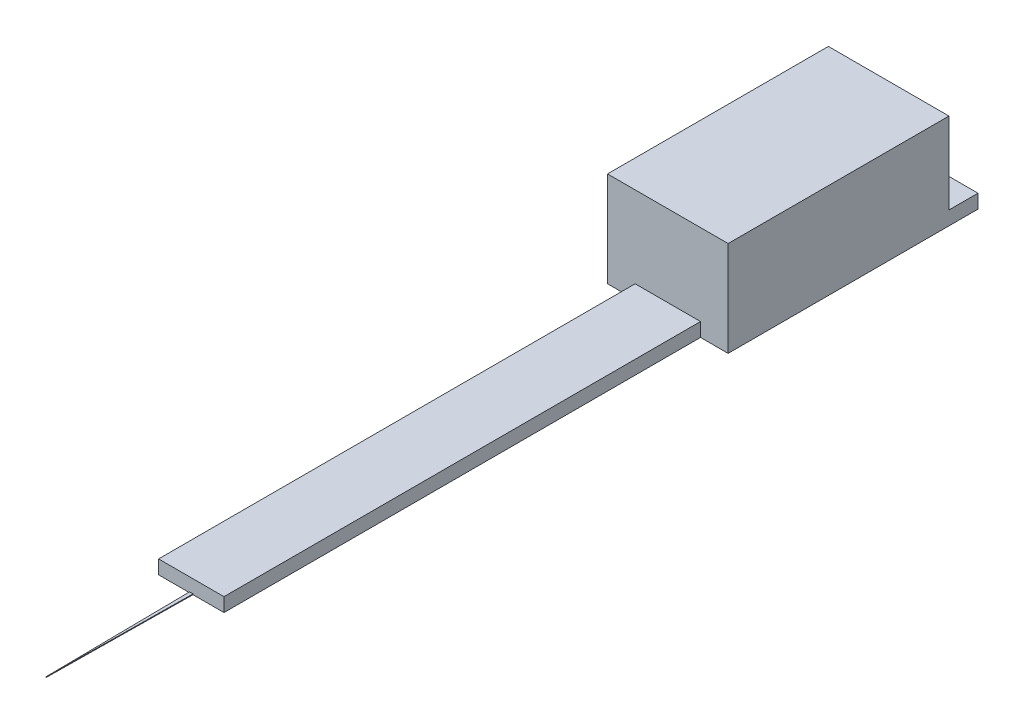
SolidWorks part; units mm, degrees
ref_plane "Front Plane" through (0, 0, 0) normal (0, 0, 1) x (1, 0, 0)
ref_plane "Top Plane" through (0, 0, 0) normal (0, 1, 0) x (1, 0, 0)
ref_plane "Right Plane" through (0, 0, 0) normal (1, 0, 0) x (0, 0, -1)
sketch "Sketch1" plane through (0, 0, 0) normal (0, 1, 0) x (1, 0, 0)
  line L0 (0, 0) -> (0.12, 10)
  line L1 (0.12, 10) -> (2.25, 10)
  line L2 (2.25, 10) -> (2.25, 42.8)
  line L3 (2.25, 42.8) -> (4.15, 42.8)
  line L4 (4.15, 42.8) -> (4.15, 60)
  line L5 (4.15, 60) -> (-4.15, 60)
  line L6 (0, -14.5849) -> (0, 93.9914) construction
  line L7 (-4.15, 42.8) -> (-4.15, 60)
  line L8 (-2.25, 42.8) -> (-4.15, 42.8)
  line L9 (-2.25, 10) -> (-2.25, 42.8)
  line L10 (-0.12, 10) -> (-2.25, 10)
  line L11 (0, 0) -> (-0.12, 10)
  point P11 (0, 60)
  dimension "D1" = 2.25
  dimension "D2" = 4.15
  dimension "D3" = 60
  dimension "D4" = 10
  dimension "D5" = 0.12
  dimension "D6" = 17.2
extrude "Extrude1" add sketch "Sketch1" along normal blind 0.05
sketch "Sketch4" plane through (0, 0.05, 0) normal (0, 1, 0) x (1, 0, 0)
  line L0 (-4.15, 60) -> (4.15, 60)
  line L1 (4.15, 60) -> (4.15, 42.8)
  line L2 (4.15, 42.8) -> (2.25, 42.8)
  line L3 (2.25, 42.8) -> (2.25, 10)
  line L4 (2.25, 10) -> (-2.25, 10)
  line L5 (-2.25, 10) -> (-2.25, 42.8)
  line L6 (-2.25, 42.8) -> (-4.15, 42.8)
  line L7 (-4.15, 42.8) -> (-4.15, 60)
extrude "Extrude2" add sketch "Sketch4" along normal blind 0.9
sketch "Sketch5" plane through (0, 0.95, 0) normal (0, 1, 0) x (1, 0, 0)
  line L0 (4.15, 42.8) -> (4.15, 60) construction
  line L1 (4.15, 58) -> (-4.15, 58)
  line L2 (4.15, 58) -> (4.15, 42.8)
  line L3 (4.15, 42.8) -> (-4.15, 42.8)
  line L4 (-4.15, 58) -> (-4.15, 42.8)
  dimension "D1" = 15.2
extrude "Extrude3" add sketch "Sketch5" along normal blind 5.6
